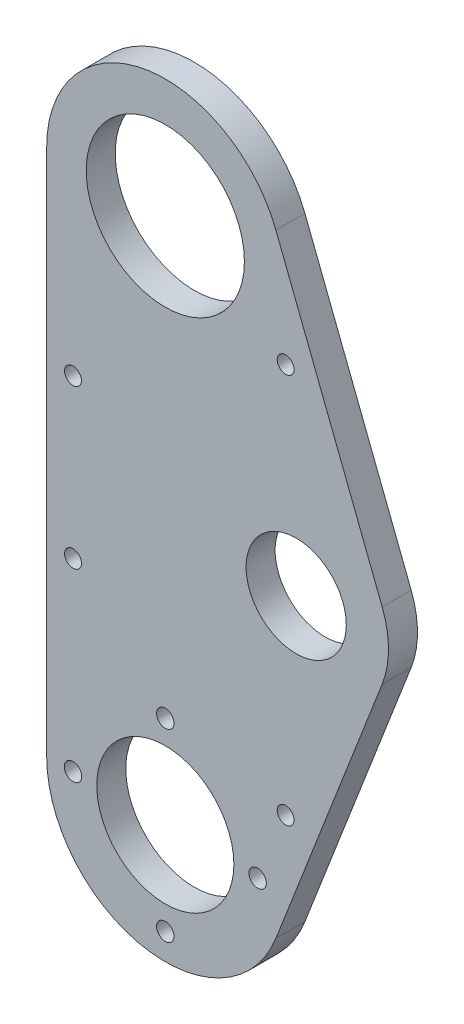
SolidWorks part; units mm, degrees
ref_plane "正面" through (0, 0, 0) normal (0, 0, 1) x (1, 0, 0)
ref_plane "平面" through (0, 0, 0) normal (0, 1, 0) x (1, 0, 0)
ref_plane "右側面" through (0, 0, 0) normal (1, 0, 0) x (0, 0, -1)
sketch "ｽｹｯﾁ1" plane through (0, 0, 0) normal (0, 0, 1) x (1, 0, 0)
  line L0 (17.5, 0) -> (-47.3168, 0)
  line L1 (-47.3168, 0) -> (-47.3168, -50)
  line L2 (16.3093, -6.3449) -> (-3.8477, -58.1577)
  circle A0 centre (0, 0) radius 9.5 construction
  arc A1 (16.3093, -6.3449) -> (17.5, 0) centre (0, 0) ccw
  arc A2 (-47.3168, -50) -> (-3.8477, -58.1577) centre (-24.8168, -50) ccw
  dimension "D1" = 19
  dimension "D2" = 8
  dimension "D3" = 45
extrude "ﾎﾞｽ - 押し出し1" add sketch "ｽｹｯﾁ1" along normal mid plane 5.5
sketch "ｽｹｯﾁ2" plane through (0, 0, 2.75) normal (0, 0, 1) x (1, 0, 0)
  circle A1 centre (0, 0) radius 9.5
  circle A2 centre (0, 0) radius 9.5
  dimension "D1" = 0
extrude "ｶｯﾄ - 押し出し1" cut sketch "ｽｹｯﾁ2" against normal through all both and the other way through all
sketch "ｽｹｯﾁ3" plane through (0, 0, 2.75) normal (0, 0, 1) x (1, 0, 0)
  circle A0 centre (-24.8168, -67.5) radius 1.65 construction
  circle A1 centre (-24.8168, -67.5) radius 1.65
extrude "ｶｯﾄ - 押し出し2" cut sketch "ｽｹｯﾁ3" against normal through all both
sketch "ｽｹｯﾁ4" plane through (0, 0, 2.75) normal (0, 0, 1) x (1, 0, 0)
  circle A0 centre (-24.8168, -50) radius 13 construction
  circle A1 centre (-24.8168, -50) radius 13
extrude "ｶｯﾄ - 押し出し3" cut sketch "ｽｹｯﾁ4" against normal through all both
pattern_circular "円形ﾊﾟﾀｰﾝ1" count 4 over 360 about axis through (-24.8168, -50, 0) along (0, 0, 1) of "ｶｯﾄ - 押し出し2"
sketch "ｽｹｯﾁ6" plane through (0, 0, 2.75) normal (0, 0, 1) x (1, 0, 0)
  circle A0 centre (-2, -37) radius 1.6
  dimension "D1" = 3.2
  dimension "D2" = 37
  dimension "D3" = 2
extrude "ｶｯﾄ - 押し出し5" cut sketch "ｽｹｯﾁ6" against normal through all
mirror "ﾐﾗｰ1" about plane through (0, 0, 0) normal (0, 1, 0) of "ｶｯﾄ - 押し出し5", "ﾎﾞｽ - 押し出し1", "ｶｯﾄ - 押し出し1"
sketch "ｽｹｯﾁ5" plane through (0, 0, 2.75) normal (0, 0, 1) x (1, 0, 0)
  circle A0 centre (-24.8168, 50) radius 15
  dimension "D1" = 30
extrude "ｶｯﾄ - 押し出し4" cut sketch "ｽｹｯﾁ5" against normal through all both
sketch "ｽｹｯﾁ7" [suppressed] plane through (0, 0, -2.75) normal (0, 0, -1) x (-1, 0, 0)
  circle A0 centre (42.3168, -15) radius 1.6 construction
  circle A1 centre (42.3168, 15) radius 1.6 construction
  circle A2 centre (42.3168, -15) radius 1.6
  circle A3 centre (42.3168, 15) radius 1.6
extrude "ｶｯﾄ - 押し出し6" [suppressed] cut sketch "ｽｹｯﾁ7" against normal through all both
sketch "ｽｹｯﾁ8" plane through (0, 0, 2.75) normal (0, 0, 1) x (1, 0, 0)
  circle A0 centre (-42.3168, 15) radius 1.6 construction
  circle A1 centre (-42.3168, -15) radius 1.6 construction
  circle A2 centre (-42.3168, 15) radius 1.6
  circle A3 centre (-42.3168, -15) radius 1.6
extrude "ｶｯﾄ - 押し出し7" cut sketch "ｽｹｯﾁ8" against normal through all both
sketch "ｽｹｯﾁ9" [suppressed] plane through (0, 0, -2.75) normal (0, 0, -1) x (-1, 0, 0)
  circle A0 centre (24.8168, 50) radius 13 construction
  circle A1 centre (24.8168, 50) radius 13
extrude "ｶｯﾄ - 押し出し8" [suppressed] cut sketch "ｽｹｯﾁ9" against normal through all both
ref_plane "平面1" [suppressed] through (-16.7547, 15.07, 86.95) normal (0, 0, 1) x (1, 0, 0)
sketch "ｽｹｯﾁ11" [suppressed] plane through (0, 0, -2.75) normal (0, 0, -1) x (-1, 0, 0)
  circle A0 centre (42.3168, 50) radius 1.65 construction
  circle A1 centre (42.3168, 50) radius 1.65
extrude "ｶｯﾄ - 押し出し9" [suppressed] cut sketch "ｽｹｯﾁ11" against normal through all both
pattern_circular "円形ﾊﾟﾀｰﾝ2" [suppressed] count 4 over 360
sketch "ｽｹｯﾁ12" [suppressed] plane through (0, 0, -2.75) normal (0, 0, -1) x (-1, 0, 0)
  circle A0 centre (24.8168, -50) radius 15
  arc A1 (3.8477, -58.1577) -> (47.3168, -50) centre (24.8168, -50) ccw construction
  dimension "D1" = 30
extrude "ｶｯﾄ - 押し出し10" [suppressed] cut sketch "ｽｹｯﾁ12" against normal through all both
sketch "ｽｹｯﾁ13" [suppressed] plane through (0, 0, -2.75) normal (0, 0, -1) x (-1, 0, 0)
  circle A0 centre (3, 36) radius 1.6 construction
  circle A1 centre (3, -36) radius 1.6 construction
  circle A2 centre (3, 36) radius 1.6
  circle A3 centre (3, -36) radius 1.6
extrude "ｶｯﾄ - 押し出し11" [suppressed] cut sketch "ｽｹｯﾁ13" against normal through all both
sketch "ｽｹｯﾁ14" [suppressed] plane through (0, 0, -2.75) normal (0, 0, -1) x (-1, 0, 0)
  line L0 (47.3168, 50) -> (47.3168, -50) construction
  circle A0 centre (35.3168, 0) radius 7.5
  dimension "D2" = 15
  dimension "D1" = 12
extrude "ｶｯﾄ - 押し出し12" [suppressed] cut sketch "ｽｹｯﾁ14" against normal through all both
